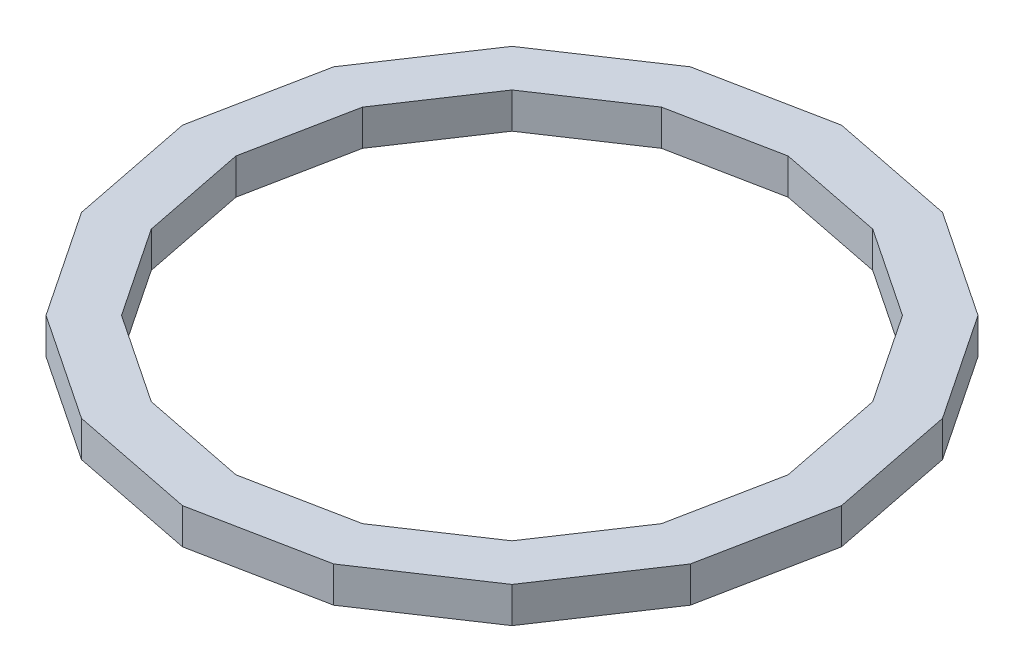
SolidWorks part; units mm, degrees
ref_plane "Front Plane" through (0, 0, 0) normal (0, 0, 1) x (1, 0, 0)
ref_plane "Top Plane" through (0, 0, 0) normal (0, 1, 0) x (1, 0, 0)
ref_plane "Right Plane" through (0, 0, 0) normal (1, 0, 0) x (0, 0, -1)
sketch "Sketch1" plane through (0, 0, 0) normal (0, 1, 0) x (1, 0, 0)
  line L1 (175.7647, 0) -> (162.3854, 67.2623)
  line L2 (162.3854, 67.2623) -> (124.2844, 124.2844)
  line L3 (124.2844, 124.2844) -> (67.2623, 162.3854)
  line L4 (67.2623, 162.3854) -> (0, 175.7647)
  line L5 (0, 175.7647) -> (-67.2623, 162.3854)
  line L6 (-67.2623, 162.3854) -> (-124.2844, 124.2844)
  line L7 (-124.2844, 124.2844) -> (-162.3854, 67.2623)
  line L8 (-162.3854, 67.2623) -> (-175.7647, 0)
  line L9 (-175.7647, 0) -> (-162.3854, -67.2623)
  line L10 (-162.3854, -67.2623) -> (-124.2844, -124.2844)
  line L11 (-124.2844, -124.2844) -> (-67.2623, -162.3854)
  line L12 (-67.2623, -162.3854) -> (0, -175.7647)
  line L13 (0, -175.7647) -> (67.2623, -162.3854)
  line L14 (67.2623, -162.3854) -> (124.2844, -124.2844)
  line L15 (124.2844, -124.2844) -> (162.3854, -67.2623)
  line L16 (162.3854, -67.2623) -> (175.7647, 0)
  line L17 (147.2774, 0) -> (136.0665, 56.3606)
  line L18 (136.0665, 56.3606) -> (104.1408, 104.1408)
  line L19 (104.1408, 104.1408) -> (56.3606, 136.0665)
  line L20 (56.3606, 136.0665) -> (0, 147.2774)
  line L21 (0, 147.2774) -> (-56.3606, 136.0665)
  line L22 (-56.3606, 136.0665) -> (-104.1408, 104.1408)
  line L23 (-104.1408, 104.1408) -> (-136.0665, 56.3606)
  line L24 (-136.0665, 56.3606) -> (-147.2774, 0)
  line L25 (-147.2774, 0) -> (-136.0665, -56.3606)
  line L26 (-136.0665, -56.3606) -> (-104.1408, -104.1408)
  line L27 (-104.1408, -104.1408) -> (-56.3606, -136.0665)
  line L28 (-56.3606, -136.0665) -> (0, -147.2774)
  line L29 (0, -147.2774) -> (56.3606, -136.0665)
  line L30 (56.3606, -136.0665) -> (104.1408, -104.1408)
  line L31 (104.1408, -104.1408) -> (136.0665, -56.3606)
  line L32 (136.0665, -56.3606) -> (147.2774, 0)
  circle A0 centre (0, 0) radius 172.3875 construction
  circle A1 centre (0, 0) radius 144.4475 construction
  dimension "D1" = 68.58
  dimension "D2" = 27.94
extrude "Boss-Extrude1" add sketch "Sketch1" along normal blind 19.05
